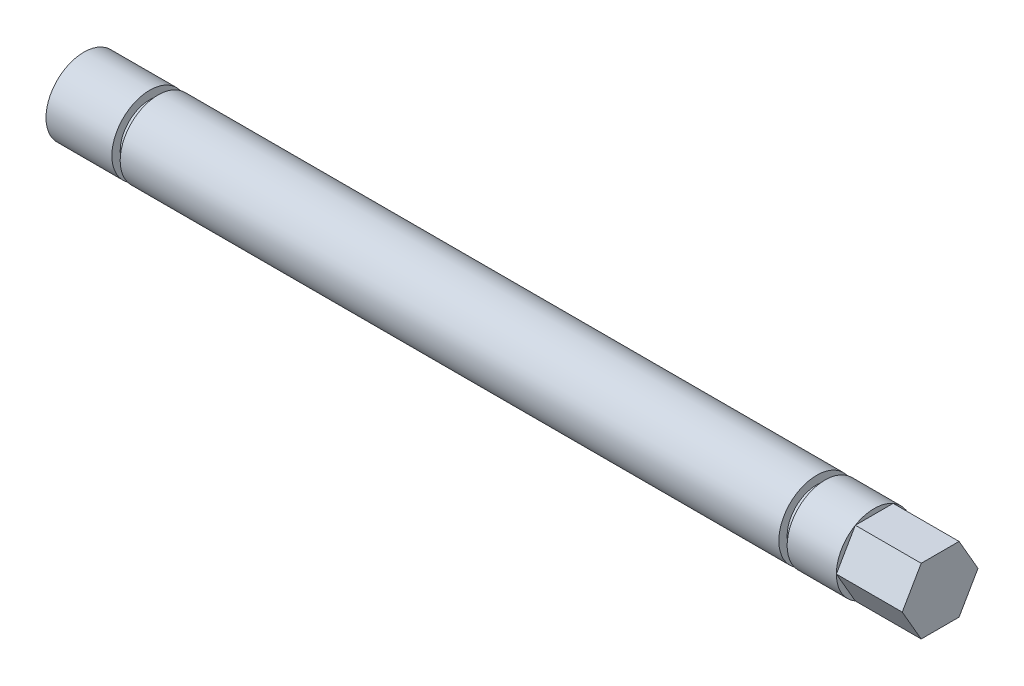
SolidWorks part; units mm, degrees
material "Chrome Stainless Steel"
ref_plane "Front Plane" through (0, 0, 0) normal (0, 0, 1) x (1, 0, 0)
ref_plane "Top Plane" through (0, 0, 0) normal (0, 1, 0) x (1, 0, 0)
ref_plane "Right Plane" through (0, 0, 0) normal (1, 0, 0) x (0, 0, -1)
sketch "Sketch1" plane through (0, 0, 0) normal (1, 0, 0) x (0, 0, -1)
  circle A0 centre (0, 0) radius 7.3025
  dimension "D1" = 14.605
extrude "Boss-Extrude1" add sketch "Sketch1" along normal blind 165.1
sketch "Sketch2" plane through (0, 0, 0) normal (0, 0, 1) x (1, 0, 0)
  line L0 (165.1, 7.3025) -> (0, 7.3025) construction
  line L1 (12.7, 7.3025) -> (14.3002, 7.3025)
  line L2 (12.7, 7.3025) -> (12.7, 5.7023)
  line L3 (12.7, 5.7023) -> (14.3002, 5.7023)
  line L4 (14.3002, 7.3025) -> (14.3002, 5.7023)
  line L5 (0, 7.3025) -> (0, -7.3025) construction
  line L6 (0, 0) -> (24.7543, 0) construction
  dimension "D1" = 1.6002
  dimension "D2" = 1.6002
  dimension "D3" = 12.7
revolve "Groove" cut sketch "Sketch2" angle 360 about L6
ref_plane "Offset Plane" through (141.3002, 0, 0) normal (-1, 0, 0) x (0, 0, 1)
sketch "Sketch3" plane through (141.3002, 0, 0) normal (-1, 0, 0) x (0, 0, 1)
  circle A0 centre (0, 0) radius 7.3025 construction
  circle A1 centre (0, 0) radius 5.7023 construction
  circle A2 centre (0, 0) radius 7.3025
  circle A3 centre (0, 0) radius 5.7023
extrude "Offset Groove" cut sketch "Sketch3" against normal blind 1.6002
sketch "Sketch4" plane through (165.1, 0, 0) normal (1, 0, 0) x (0, 0, -1)
  line L1 (3.6512, 6.3242) -> (-3.6513, 6.3242)
  line L2 (-3.6513, 6.3242) -> (-7.3025, 0)
  line L3 (-7.3025, 0) -> (-3.6512, -6.3242)
  line L4 (-3.6512, -6.3242) -> (3.6512, -6.3242)
  line L5 (3.6512, -6.3242) -> (7.3025, 0)
  line L6 (7.3025, 0) -> (3.6512, 6.3242)
  circle A0 centre (0, 0) radius 7.3025 construction
  circle A1 centre (0, 0) radius 7.3025 construction
extrude "Hex Cut" cut sketch "Sketch4" against normal blind 12.7 flip side to cut
